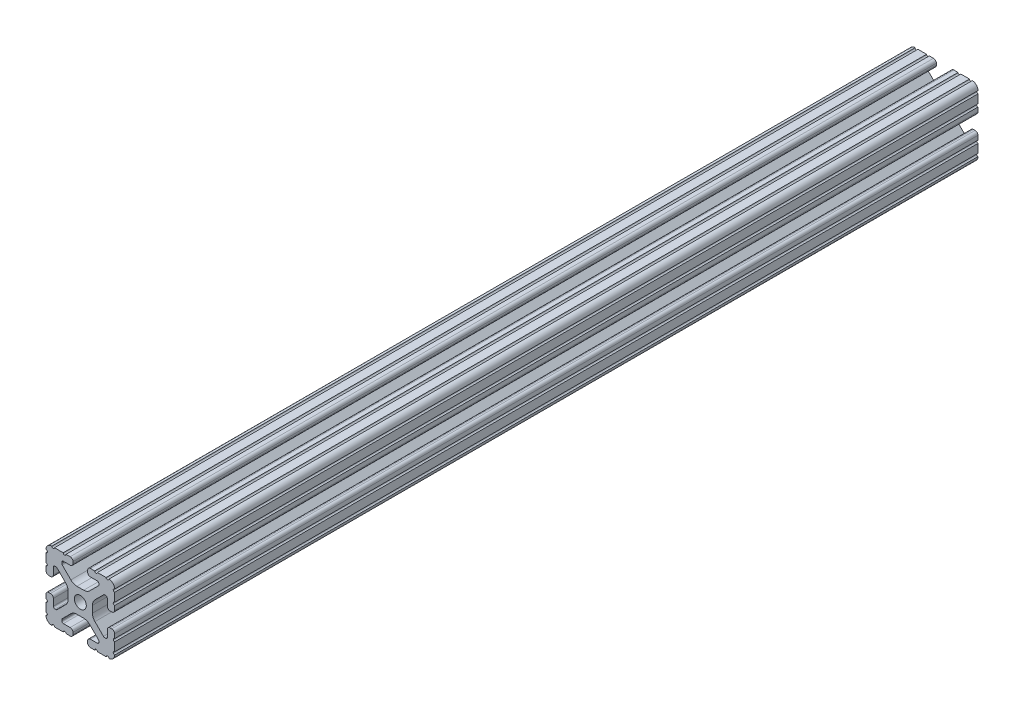
SolidWorks part; units mm, degrees
material "6105-T5 Aluminum"
ref_plane "Front Plane" through (0, 0, 0) normal (0, 0, 1) x (1, 0, 0)
ref_plane "Top Plane" through (0, 0, 0) normal (0, 1, 0) x (1, 0, 0)
ref_plane "Right Plane" through (0, 0, 0) normal (1, 0, 0) x (0, 0, -1)
sketch "Sketch1" plane through (0, 0, 0) normal (0, 0, 1) x (1, 0, 0)
  line L0 (-14.097, 10.287) -> (-13.5289, 10.287)
  line L1 (-12.9003, 10.0266) -> (-8.1292, 5.2555)
  line L2 (-6.738, 1.8969) -> (-6.738, -1.8969)
  line L3 (-8.1292, -5.2555) -> (-12.9003, -10.0266)
  line L4 (-13.5289, -10.287) -> (-14.097, -10.287)
  line L5 (-14.986, -9.398) -> (-14.986, -5.6388)
  line L6 (-16.5608, -4.064) -> (-17.4752, -4.064)
  line L7 (-19.05, -5.6388) -> (-19.05, -7.9756)
  line L8 (-19.05, -9.4996) -> (-19.05, -14.3256)
  line L9 (-19.05, -15.8496) -> (-19.05, -15.875)
  line L10 (-15.875, -19.05) -> (-15.8496, -19.05)
  line L11 (-14.3256, -19.05) -> (-9.4996, -19.05)
  line L12 (-7.9756, -19.05) -> (-5.6388, -19.05)
  line L13 (-4.064, -17.4752) -> (-4.064, -16.5608)
  line L14 (-5.6388, -14.986) -> (-9.398, -14.986)
  line L15 (-10.287, -14.097) -> (-10.287, -13.5289)
  line L16 (-10.0266, -12.9003) -> (-5.2555, -8.1292)
  line L17 (-1.8969, -6.738) -> (1.8969, -6.738)
  line L18 (5.2555, -8.1292) -> (10.0266, -12.9003)
  line L19 (10.287, -13.5289) -> (10.287, -14.097)
  line L20 (9.398, -14.986) -> (5.6388, -14.986)
  line L21 (4.064, -16.5608) -> (4.064, -17.4752)
  line L22 (5.6388, -19.05) -> (7.9756, -19.05)
  line L23 (9.4996, -19.05) -> (14.3256, -19.05)
  line L24 (15.8496, -19.05) -> (15.875, -19.05)
  line L25 (19.05, -15.875) -> (19.05, -15.8496)
  line L26 (19.05, -14.3256) -> (19.05, -9.4996)
  line L27 (19.05, -7.9756) -> (19.05, -5.6388)
  line L28 (17.4752, -4.064) -> (16.5608, -4.064)
  line L29 (14.986, -5.6388) -> (14.986, -9.398)
  line L30 (14.097, -10.287) -> (13.5289, -10.287)
  line L31 (12.9003, -10.0266) -> (8.1292, -5.2555)
  line L32 (6.738, -1.8969) -> (6.738, 1.8969)
  line L33 (8.1292, 5.2555) -> (12.9003, 10.0266)
  line L34 (13.5289, 10.287) -> (14.097, 10.287)
  line L35 (14.986, 9.398) -> (14.986, 5.6388)
  line L36 (16.5608, 4.064) -> (17.4752, 4.064)
  line L37 (19.05, 5.6388) -> (19.05, 7.9756)
  line L38 (19.05, 9.4996) -> (19.05, 14.3256)
  line L39 (19.05, 15.8496) -> (19.05, 15.875)
  line L40 (15.875, 19.05) -> (15.8496, 19.05)
  line L41 (14.3256, 19.05) -> (9.4996, 19.05)
  line L42 (7.9756, 19.05) -> (5.6388, 19.05)
  line L43 (4.064, 17.4752) -> (4.064, 16.5608)
  line L44 (5.6388, 14.986) -> (9.398, 14.986)
  line L45 (10.287, 14.097) -> (10.287, 13.5289)
  line L46 (10.0266, 12.9003) -> (5.2555, 8.1292)
  line L47 (1.8969, 6.738) -> (-1.8969, 6.738)
  line L48 (-5.2555, 8.1292) -> (-10.0266, 12.9003)
  line L49 (-10.287, 13.5289) -> (-10.287, 14.097)
  line L50 (-9.398, 14.986) -> (-5.6388, 14.986)
  line L51 (-4.064, 16.5608) -> (-4.064, 17.4752)
  line L52 (-5.6388, 19.05) -> (-7.9756, 19.05)
  line L53 (-9.4996, 19.05) -> (-14.3256, 19.05)
  line L54 (-15.8496, 19.05) -> (-15.875, 19.05)
  line L55 (-19.05, 15.875) -> (-19.05, 15.8496)
  line L56 (-19.05, 14.3256) -> (-19.05, 9.4996)
  line L57 (-19.05, 7.9756) -> (-19.05, 5.6388)
  line L58 (-17.4752, 4.064) -> (-16.5608, 4.064)
  line L59 (-14.986, 5.6388) -> (-14.986, 9.398)
  circle A0 centre (0, 0) radius 3.3274
  arc A1 (-14.097, 10.287) -> (-14.986, 9.398) centre (-14.097, 9.398) ccw
  arc A2 (-12.9003, 10.0266) -> (-13.5289, 10.287) centre (-13.5289, 9.398) ccw
  arc A3 (-6.738, 1.8969) -> (-8.1292, 5.2555) centre (-11.4878, 1.8969) ccw
  arc A4 (-8.1292, -5.2555) -> (-6.738, -1.8969) centre (-11.4878, -1.8969) ccw
  arc A5 (-13.5289, -10.287) -> (-12.9003, -10.0266) centre (-13.5289, -9.398) ccw
  arc A6 (-14.986, -9.398) -> (-14.097, -10.287) centre (-14.097, -9.398) ccw
  arc A7 (-14.986, -5.6388) -> (-16.5608, -4.064) centre (-16.5608, -5.6388) ccw
  arc A8 (-17.4752, -4.064) -> (-19.05, -5.6388) centre (-17.4752, -5.6388) ccw
  arc A9 (-19.05, -9.4996) -> (-19.05, -7.9756) centre (-19.05, -8.7376) ccw
  arc A10 (-19.05, -15.8496) -> (-19.05, -14.3256) centre (-19.05, -15.0876) ccw
  arc A11 (-19.05, -15.875) -> (-15.875, -19.05) centre (-15.875, -15.875) ccw
  arc A12 (-14.3256, -19.05) -> (-15.8496, -19.05) centre (-15.0876, -19.05) ccw
  arc A13 (-7.9756, -19.05) -> (-9.4996, -19.05) centre (-8.7376, -19.05) ccw
  arc A14 (-5.6388, -19.05) -> (-4.064, -17.4752) centre (-5.6388, -17.4752) ccw
  arc A15 (-4.064, -16.5608) -> (-5.6388, -14.986) centre (-5.6388, -16.5608) ccw
  arc A16 (-10.287, -14.097) -> (-9.398, -14.986) centre (-9.398, -14.097) ccw
  arc A17 (-10.0266, -12.9003) -> (-10.287, -13.5289) centre (-9.398, -13.5289) ccw
  arc A18 (-1.8969, -6.738) -> (-5.2555, -8.1292) centre (-1.8969, -11.4878) ccw
  arc A19 (5.2555, -8.1292) -> (1.8969, -6.738) centre (1.8969, -11.4878) ccw
  arc A20 (10.287, -13.5289) -> (10.0266, -12.9003) centre (9.398, -13.5289) ccw
  arc A21 (9.398, -14.986) -> (10.287, -14.097) centre (9.398, -14.097) ccw
  arc A22 (5.6388, -14.986) -> (4.064, -16.5608) centre (5.6388, -16.5608) ccw
  arc A23 (4.064, -17.4752) -> (5.6388, -19.05) centre (5.6388, -17.4752) ccw
  arc A24 (9.4996, -19.05) -> (7.9756, -19.05) centre (8.7376, -19.05) ccw
  arc A25 (15.8496, -19.05) -> (14.3256, -19.05) centre (15.0876, -19.05) ccw
  arc A26 (15.875, -19.05) -> (19.05, -15.875) centre (15.875, -15.875) ccw
  arc A27 (19.05, -14.3256) -> (19.05, -15.8496) centre (19.05, -15.0876) ccw
  arc A28 (19.05, -7.9756) -> (19.05, -9.4996) centre (19.05, -8.7376) ccw
  arc A29 (19.05, -5.6388) -> (17.4752, -4.064) centre (17.4752, -5.6388) ccw
  arc A30 (16.5608, -4.064) -> (14.986, -5.6388) centre (16.5608, -5.6388) ccw
  arc A31 (14.097, -10.287) -> (14.986, -9.398) centre (14.097, -9.398) ccw
  arc A32 (12.9003, -10.0266) -> (13.5289, -10.287) centre (13.5289, -9.398) ccw
  arc A33 (6.738, -1.8969) -> (8.1292, -5.2555) centre (11.4878, -1.8969) ccw
  arc A34 (8.1292, 5.2555) -> (6.738, 1.8969) centre (11.4878, 1.8969) ccw
  arc A35 (13.5289, 10.287) -> (12.9003, 10.0266) centre (13.5289, 9.398) ccw
  arc A36 (14.986, 9.398) -> (14.097, 10.287) centre (14.097, 9.398) ccw
  arc A37 (14.986, 5.6388) -> (16.5608, 4.064) centre (16.5608, 5.6388) ccw
  arc A38 (17.4752, 4.064) -> (19.05, 5.6388) centre (17.4752, 5.6388) ccw
  arc A39 (19.05, 9.4996) -> (19.05, 7.9756) centre (19.05, 8.7376) ccw
  arc A40 (19.05, 15.8496) -> (19.05, 14.3256) centre (19.05, 15.0876) ccw
  arc A41 (19.05, 15.875) -> (15.875, 19.05) centre (15.875, 15.875) ccw
  arc A42 (14.3256, 19.05) -> (15.8496, 19.05) centre (15.0876, 19.05) ccw
  arc A43 (7.9756, 19.05) -> (9.4996, 19.05) centre (8.7376, 19.05) ccw
  arc A44 (5.6388, 19.05) -> (4.064, 17.4752) centre (5.6388, 17.4752) ccw
  arc A45 (4.064, 16.5608) -> (5.6388, 14.986) centre (5.6388, 16.5608) ccw
  arc A46 (10.287, 14.097) -> (9.398, 14.986) centre (9.398, 14.097) ccw
  arc A47 (10.0266, 12.9003) -> (10.287, 13.5289) centre (9.398, 13.5289) ccw
  arc A48 (1.8969, 6.738) -> (5.2555, 8.1292) centre (1.8969, 11.4878) ccw
  arc A49 (-5.2555, 8.1292) -> (-1.8969, 6.738) centre (-1.8969, 11.4878) ccw
  arc A50 (-10.287, 13.5289) -> (-10.0266, 12.9003) centre (-9.398, 13.5289) ccw
  arc A51 (-9.398, 14.986) -> (-10.287, 14.097) centre (-9.398, 14.097) ccw
  arc A52 (-5.6388, 14.986) -> (-4.064, 16.5608) centre (-5.6388, 16.5608) ccw
  arc A53 (-4.064, 17.4752) -> (-5.6388, 19.05) centre (-5.6388, 17.4752) ccw
  arc A54 (-9.4996, 19.05) -> (-7.9756, 19.05) centre (-8.7376, 19.05) ccw
  arc A55 (-15.8496, 19.05) -> (-14.3256, 19.05) centre (-15.0876, 19.05) ccw
  arc A56 (-15.875, 19.05) -> (-19.05, 15.875) centre (-15.875, 15.875) ccw
  arc A57 (-19.05, 14.3256) -> (-19.05, 15.8496) centre (-19.05, 15.0876) ccw
  arc A58 (-19.05, 7.9756) -> (-19.05, 9.4996) centre (-19.05, 8.7376) ccw
  arc A59 (-19.05, 5.6388) -> (-17.4752, 4.064) centre (-17.4752, 5.6388) ccw
  arc A60 (-16.5608, 4.064) -> (-14.986, 5.6388) centre (-16.5608, 5.6388) ccw
extrude "Boss-Extrude1" add sketch "Sketch1" along normal blind 479.425
